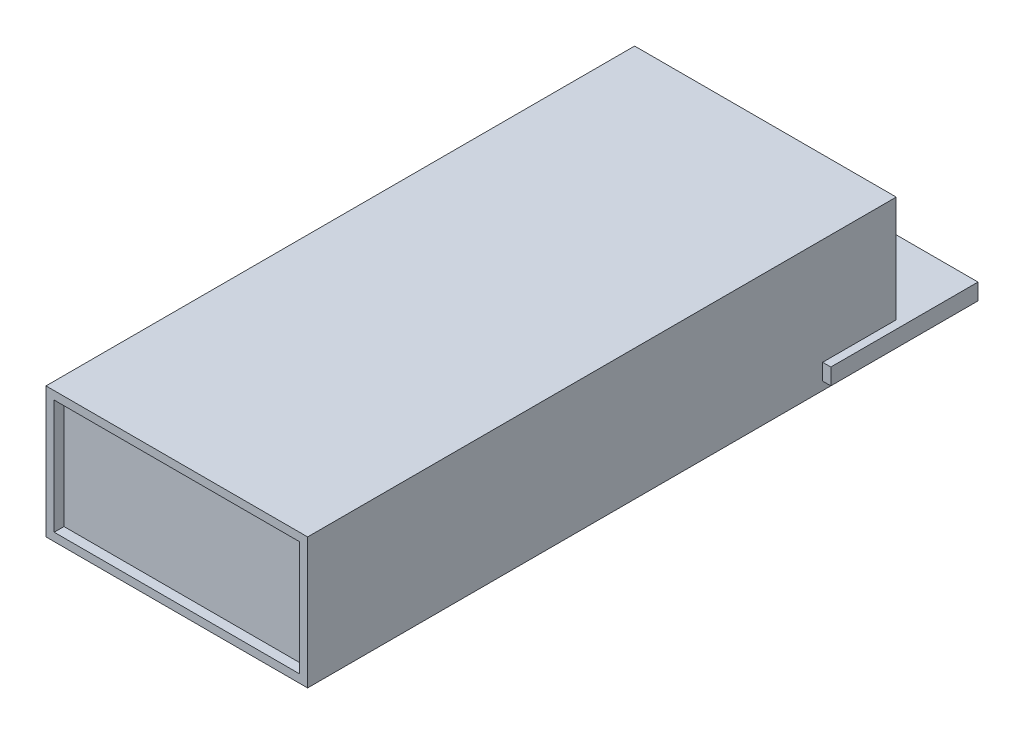
SolidWorks part; units mm, degrees
ref_plane "前视基准面" through (0, 0, 0) normal (0, 0, 1) x (1, 0, 0)
ref_plane "上视基准面" through (0, 0, 0) normal (0, 1, 0) x (1, 0, 0)
ref_plane "右视基准面" through (0, 0, 0) normal (1, 0, 0) x (0, 0, -1)
other "Configuration Table"
sketch "草图1" plane through (0, 0, 0) normal (0, 0, 1) x (1, 0, 0)
  line L1 (-400, -200) -> (400, -200)
  line L2 (-400, -200) -> (-400, 200)
  line L3 (-400, 200) -> (400, 200)
  line L4 (400, -200) -> (400, 200)
  line L5 (-400, -200) -> (400, 200) construction
  line L6 (-400, 200) -> (400, -200) construction
extrude "凸台-拉伸1" add sketch "草图1" along normal blind 1800
sketch "草图2" plane through (0, 0, 1800) normal (0, 0, 1) x (1, 0, 0)
  line L1 (-375, -175) -> (375, -175)
  line L2 (-375, -175) -> (-375, 175)
  line L3 (-375, 175) -> (375, 175)
  line L4 (375, -175) -> (375, 175)
  line L5 (-375, -175) -> (375, 175) construction
  line L6 (-375, 175) -> (375, -175) construction
extrude "切除-拉伸1" cut sketch "草图2" against normal blind 30
sketch "草图3" plane through (0, 0, 0) normal (0, 0, 1) x (1, 0, 0)
  line L0 (375, -175) -> (375, 175) construction
  line L1 (-375, -190) -> (375, -190)
  line L2 (-375, -190) -> (-375, -170)
  line L3 (-375, -170) -> (375, -170)
  line L4 (375, -190) -> (375, -170)
  line L5 (-375, -190) -> (375, -170) construction
  line L6 (-375, -170) -> (375, -190) construction
  point P0 (0, -180)
extrude "凸台-拉伸2" add sketch "草图3" along normal blind 800
sketch "草图4" plane through (0, 0, 0) normal (0, 0, 1) x (1, 0, 0)
  circle A0 centre (300, -180) radius 20
extrude "凸台-拉伸3" add sketch "草图4" along normal blind 50
sketch "草图5" plane through (0, -175, 0) normal (0, 1, 0) x (1, 0, 0)
  line L1 (-425, -225) -> (425, -225)
  line L2 (-425, -225) -> (-425, 225)
  line L3 (-425, 225) -> (425, 225)
  line L4 (425, -225) -> (425, 225)
  line L5 (-425, -225) -> (425, 225) construction
  line L6 (-425, 225) -> (425, -225) construction
extrude "凸台-拉伸4" add sketch "草图5" along normal blind 50
